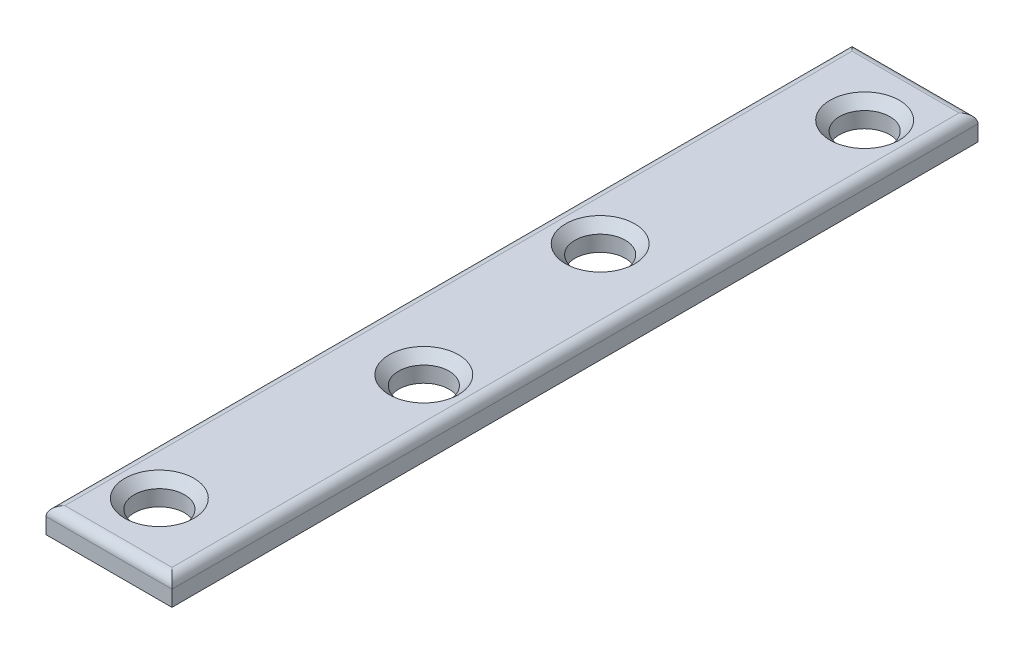
SolidWorks part; units mm, degrees
ref_plane "Front Plane" through (0, 0, 0) normal (0, 0, 1) x (1, 0, 0)
ref_plane "Top Plane" through (0, 0, 0) normal (0, 1, 0) x (1, 0, 0)
ref_plane "Right Plane" through (0, 0, 0) normal (1, 0, 0) x (0, 0, -1)
sketch "Sketch1" plane through (0, 0, 0) normal (0, 1, 0) x (1, 0, 0)
  line L1 (0, 0) -> (15.875, 0)
  line L2 (0, 0) -> (0, 101.6)
  line L3 (0, 101.6) -> (15.875, 101.6)
  line L4 (15.875, 0) -> (15.875, 101.6)
  dimension "D1" = 15.875
  dimension "D2" = 101.6
extrude "Boss-Extrude1" add sketch "Sketch1" along normal blind 3.175
sketch "Sketch2" plane through (0, 3.175, 0) normal (0, 1, 0) x (1, 0, 0)
  line L0 (0, 101.6) -> (0, 0) construction
  line L1 (15.875, 0) -> (15.875, 101.6) construction
  line L2 (15.875, 101.6) -> (0, 101.6) construction
  line L3 (0, 0) -> (15.875, 0) construction
  circle A0 centre (6.35, 63.5) radius 3.175
  circle A1 centre (9.525, 93.6625) radius 3.175
  circle A2 centre (9.525, 38.1) radius 3.175
  circle A3 centre (6.35, 7.9375) radius 3.175
  dimension "D1" = 6.35
  dimension "D2" = 6.35
  dimension "D3" = 6.35
  dimension "D4" = 6.35
  dimension "D5" = 6.35
  dimension "D6" = 6.35
  dimension "D7" = 7.9375
  dimension "D8" = 38.1
  dimension "D9" = 38.1
  dimension "D10" = 6.35
  dimension "D11" = 6.35
  dimension "D12" = 7.9375
extrude "Cut-Extrude1" cut sketch "Sketch2" against normal through all
chamfer "Chamfer1" distance 1.1906 angle 45 4 edges at (6.35, 3.175, -4.7625) (9.525, 3.175, -34.925) (9.525, 3.175, -90.4875) (6.35, 3.175, -60.325)
fillet "Fillet1" radius 1.1906 4 edges at (7.9375, 3.175, -101.6) (15.875, 3.175, -50.8) (7.9375, 3.175, 0) (0, 3.175, -50.8)
